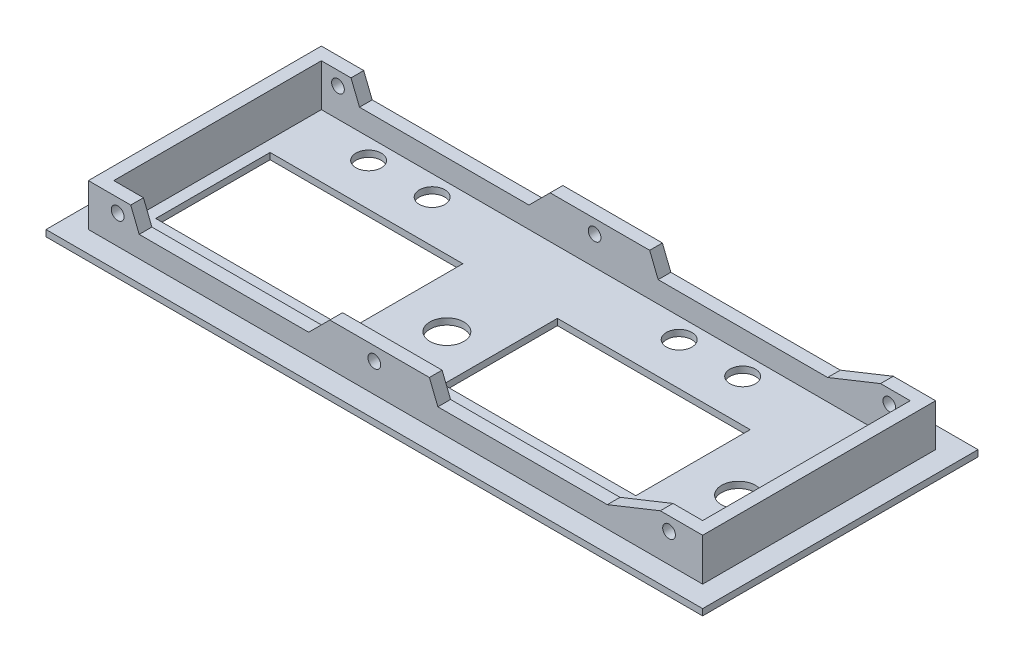
SolidWorks part; units mm, degrees
ref_plane "Front Plane" through (0, 0, 0) normal (0, 0, 1) x (1, 0, 0)
ref_plane "Top Plane" through (0, 0, 0) normal (0, 1, 0) x (1, 0, 0)
ref_plane "Right Plane" through (0, 0, 0) normal (1, 0, 0) x (0, 0, -1)
sketch "Sketch1" plane through (0, 0, 0) normal (0, 1, 0) x (1, 0, 0)
  line L1 (-80.5714, 37.7857) -> (74.4286, 37.7857)
  line L2 (-80.5714, 37.7857) -> (-80.5714, -27.2143)
  line L3 (-80.5714, -27.2143) -> (74.4286, -27.2143)
  line L4 (74.4286, 37.7857) -> (74.4286, -27.2143)
  dimension "D1" = 65
  dimension "D2" = 155
extrude "Boss-Extrude1" add sketch "Sketch1" along normal blind 1.5
sketch "Sketch2" plane through (0, 1.5, 0) normal (0, 1, 0) x (1, 0, 0)
  line L0 (74.4286, 37.7857) -> (-80.5714, 37.7857) construction
  line L1 (-75.5714, 32.7857) -> (69.4286, 32.7857)
  line L2 (-75.5714, 32.7857) -> (-75.5714, -22.2143)
  line L3 (-75.5714, -22.2143) -> (69.4286, -22.2143)
  line L4 (69.4286, 32.7857) -> (69.4286, -22.2143)
  line L5 (-80.5714, 37.7857) -> (-80.5714, -27.2143) construction
  line L6 (-80.5714, -27.2143) -> (74.4286, -27.2143) construction
  line L7 (74.4286, -27.2143) -> (74.4286, 37.7857) construction
  line L9 (-72.5714, 29.7857) -> (66.4286, 29.7857)
  line L10 (-72.5714, 29.7857) -> (-72.5714, -19.2143)
  line L11 (-72.5714, -19.2143) -> (66.4286, -19.2143)
  line L12 (66.4286, 29.7857) -> (66.4286, -19.2143)
  dimension "D1" = 5
  dimension "D2" = 5
  dimension "D3" = 5
  dimension "D4" = 5
  dimension "D5" = 3
  dimension "D6" = 3
  dimension "D7" = 3
  dimension "D8" = 3
extrude "Boss-Extrude2" add sketch "Sketch2" along normal blind 10
sketch "Sketch4" plane through (0, 0, 22.2143) normal (0, 0, 1) x (1, 0, 0)
  line L0 (-65.5714, 11.5) -> (-63.5714, 6.5)
  line L1 (-75.5714, 11.5) -> (69.4286, 11.5) construction
  line L2 (-63.5714, 6.5) -> (-23.5714, 6.5)
  line L3 (-23.5714, 6.5) -> (-18.5714, 11.5)
  line L4 (4.9286, 11.5) -> (59.4286, 11.5)
  line L5 (4.9286, 11.5) -> (6.9286, 6.5)
  line L6 (6.9286, 6.5) -> (46.9286, 6.5)
  line L7 (46.9286, 6.5) -> (59.4286, 11.5)
  line L8 (-18.5714, 11.5) -> (-65.5714, 11.5)
  line L9 (4.9286, 11.5) -> (59.4286, 11.5)
  line L10 (59.4286, 11.5) -> (52.1881, 12.9451)
  dimension "D1" = 10
  dimension "D2" = 10
  dimension "D3" = 5
  dimension "D4" = 40
  dimension "D5" = 40
  dimension "D6" = 5
extrude "Cut-Extrude1" cut sketch "Sketch4" against normal blind 91
sketch "Sketch5" plane through (0, 0, 0) normal (0, -1, 0) x (1, 0, 0)
  line L1 (-2.0441, 12.0135) -> (43.4559, 12.0135)
  line L2 (-2.0441, 12.0135) -> (-2.0441, -14.9865)
  line L3 (-2.0441, -14.9865) -> (43.4559, -14.9865)
  line L4 (43.4559, 12.0135) -> (43.4559, -14.9865)
  line L5 (-69.8754, 12.0135) -> (-24.3754, 12.0135)
  line L6 (-69.8754, 12.0135) -> (-69.8754, -14.9865)
  line L7 (-69.8754, -14.9865) -> (-24.3754, -14.9865)
  line L8 (-24.3754, 12.0135) -> (-24.3754, -14.9865)
  circle A0 centre (16.6871, -24.9865) radius 3
  circle A1 centre (31.6871, -24.9804) radius 3
  circle A2 centre (55.4559, -0.235) radius 4
  circle A3 centre (-12.3754, 0.7831) radius 4
  circle A4 centre (-56.6168, -24.9865) radius 3
  circle A5 centre (-41.6168, -24.9865) radius 3
  dimension "D5" = 15
  dimension "D6" = 15
  dimension "D9" = 6
  dimension "D10" = 6
  dimension "D13" = 6
  dimension "D14" = 6
  dimension "D1" = 45.5
  dimension "D2" = 45.5
  dimension "D3" = 27
  dimension "D4" = 27
  dimension "D7" = 10
  dimension "D8" = 10
  dimension "D11" = 12
  dimension "D12" = 12
extrude "Cut-Extrude2" cut sketch "Sketch5" against normal blind 91
sketch "Sketch6" plane through (0, 0, 22.2143) normal (0, 0, 1) x (1, 0, 0)
  circle A0 centre (-8.0744, 8.312) radius 1.5
  circle A1 centre (61.497, 8.312) radius 1.5
  circle A2 centre (-68.65, 8.3) radius 1.5
extrude "Cut-Extrude3" cut sketch "Sketch6" against normal blind 91
